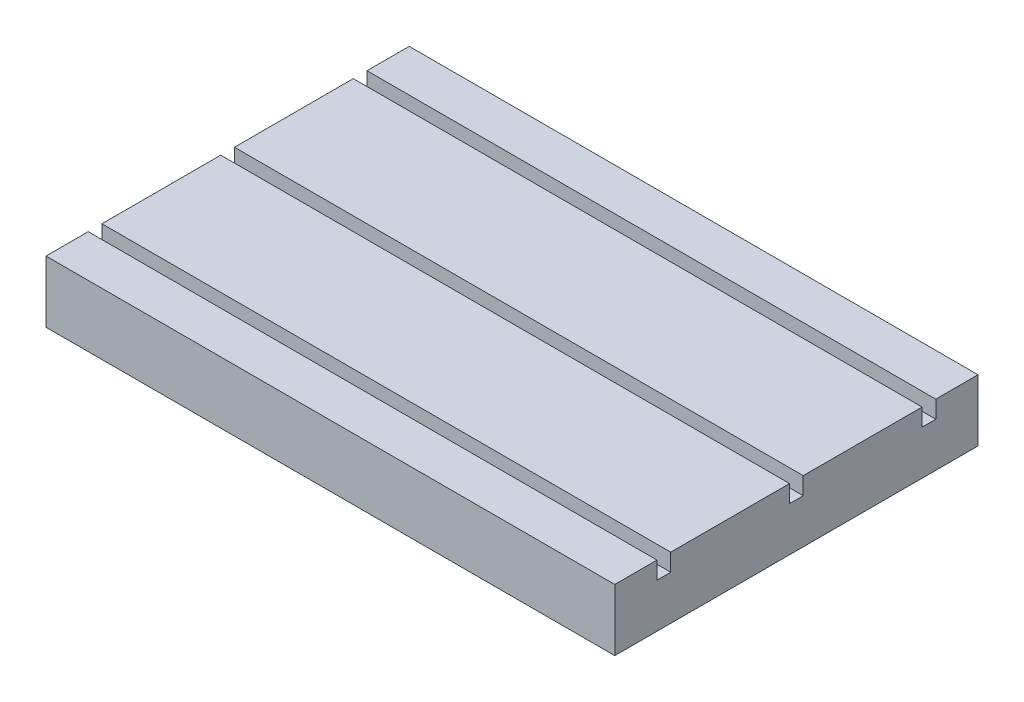
SolidWorks part; units mm, degrees
ref_plane "Front Plane" through (0, 0, 0) normal (0, 0, 1) x (1, 0, 0)
ref_plane "Top Plane" through (0, 0, 0) normal (0, 1, 0) x (1, 0, 0)
ref_plane "Right Plane" through (0, 0, 0) normal (1, 0, 0) x (0, 0, -1)
sketch "Sketch1" plane through (0, 0, 0) normal (0, 1, 0) x (1, 0, 0)
  line L1 (0, 0) -> (83, 0)
  line L2 (0, 0) -> (0, -53)
  line L3 (0, -53) -> (83, -53)
  line L4 (83, 0) -> (83, -53)
  dimension "D1" = 83
  dimension "D2" = 53
extrude "Boss-Extrude1" add sketch "Sketch1" along normal blind 9
sketch "Sketch2" plane through (0, 9, 0) normal (0, 1, 0) x (1, 0, 0)
  line L1 (0, 0) -> (0, -53) construction
  line L2 (83, -53) -> (83, 0) construction
  line L3 (83, 0) -> (0, 0) construction
  line L5 (0, -27.5) -> (0, -25.5)
  line L6 (0, -25.5) -> (83, -25.5)
  line L7 (83, -26.5) -> (83, -25.5)
  line L8 (0, -6.1593) -> (83, -6.1593)
  line L9 (0, -6.1593) -> (0, -8.1593)
  line L10 (0, -8.1593) -> (83, -8.1593)
  line L11 (83, -6.1593) -> (83, -8.1593)
  line L12 (83, -26.5) -> (83, -27.5)
  line L13 (0, -27.5) -> (83, -27.5)
  line L14 (83, -46.8407) -> (83, -44.8407)
  line L15 (0, -46.8407) -> (0, -44.8407)
  line L16 (0, -44.8407) -> (83, -44.8407)
  line L17 (0, -46.8407) -> (83, -46.8407)
  dimension "D2" = 2
  dimension "D3" = 6.1593
extrude "Cut-Extrude1" cut sketch "Sketch2" against normal blind 2.54 contours L16 L14 L17 L15 | L8 L11 L10 L9 | L6 L7 L12 L13 L5
